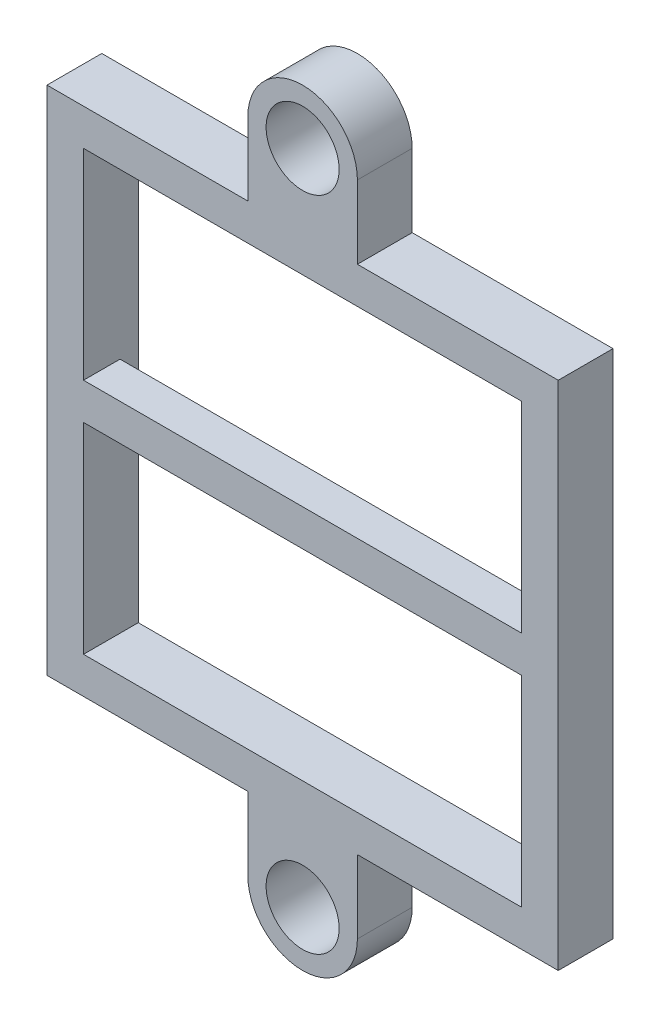
SolidWorks part; units mm, degrees
ref_plane "前视基准面" through (0, 0, 0) normal (0, 0, 1) x (1, 0, 0)
ref_plane "上视基准面" through (0, 0, 0) normal (0, 1, 0) x (1, 0, 0)
ref_plane "右视基准面" through (0, 0, 0) normal (1, 0, 0) x (0, 0, -1)
sketch "草图6" plane through (0, 0, 0) normal (0, 0, 1) x (1, 0, 0)
  line L0 (-7, 7) -> (7, 7)
  line L1 (-6, -6) -> (6, -6)
  line L2 (-6, -6) -> (-6, 6)
  line L3 (-6, 6) -> (6, 6)
  line L4 (6, -6) -> (6, 6)
  line L5 (-6, -6) -> (6, 6) construction
  line L6 (-6, 6) -> (6, -6) construction
  line L7 (7, -7) -> (7, 7)
  line L8 (-7, -7) -> (7, -7)
  line L9 (-7, -7) -> (-7, 7)
  point P0 (0, 0)
  dimension "D1" = 12
  dimension "D3" = 12
  dimension "D2" = 1
extrude "凸台-拉伸3" add sketch "草图6" along normal blind 1.5
sketch "草图7" plane through (0, -7, 0) normal (0, -1, 0) x (1, 0, 0)
  line L0 (-7, 1.5) -> (7, 1.5) construction
  line L1 (-1.5, 0) -> (1.5, 0)
  line L2 (-1.5, 0) -> (-1.5, 1.5)
  line L3 (-1.5, 1.5) -> (1.5, 1.5)
  line L4 (1.5, 0) -> (1.5, 1.5)
  line L5 (-1.5, 0) -> (1.5, 1.5) construction
  line L6 (-1.5, 1.5) -> (1.5, 0) construction
  line L7 (-7, 0) -> (7, 0) construction
  point P0 (0, 0.75)
  dimension "D1" = 3
extrude "凸台-拉伸4" add sketch "草图7" along normal blind 3.5
sketch "草图8" plane through (0, 0, 1.5) normal (0, 0, 1) x (1, 0, 0)
  line L0 (1.5, -10.5) -> (1.5, -7) construction
  line L3 (1.5, -10.5) -> (-1.5, -10.5) construction
  line L4 (-1.5, -10.5) -> (-1.5, -7) construction
  line L5 (1.5, -9) -> (1.5, -10.5)
  line L6 (1.5, -10.5) -> (-1.5, -10.5)
  line L7 (-1.5, -10.5) -> (-1.5, -9)
  circle A0 centre (0, -9) radius 1.5
  line M4 (-1.5, -7) -> (-1.5, -10.5)
  line M5 (-1.5, -10.5) -> (1.5, -10.5)
  line M6 (1.5, -10.5) -> (1.5, -7)
extrude "切除-拉伸3" cut sketch "草图8" against normal blind 4 contours A0 M4 M5 | A0 L6 M6
sketch "草图11" plane through (0, 0, 1.5) normal (0, 0, 1) x (1, 0, 0)
  circle A0 centre (0, -9) radius 1
  dimension "D1" = 9
extrude "切除-拉伸5" cut sketch "草图11" against normal blind 4
mirror "镜向1" about plane through (0, 0, 0) normal (0, 1, 0) of "切除-拉伸3", "凸台-拉伸4", "切除-拉伸5"
sketch "草图12" plane through (0, 0, 1.5) normal (0, 0, 1) x (1, 0, 0)
  line L0 (-6, 6) -> (-6, -6) construction
  line L1 (6, -0.5) -> (-6, -0.5)
  line L2 (6, -0.5) -> (6, 0.5)
  line L3 (6, 0.5) -> (-6, 0.5)
  line L4 (-6, -0.5) -> (-6, 0.5)
  line L5 (6, -0.5) -> (-6, 0.5) construction
  line L6 (6, 0.5) -> (-6, -0.5) construction
  point P0 (0, 0)
  dimension "D1" = 1
extrude "凸台-拉伸5" add sketch "草图12" against normal blind 1
